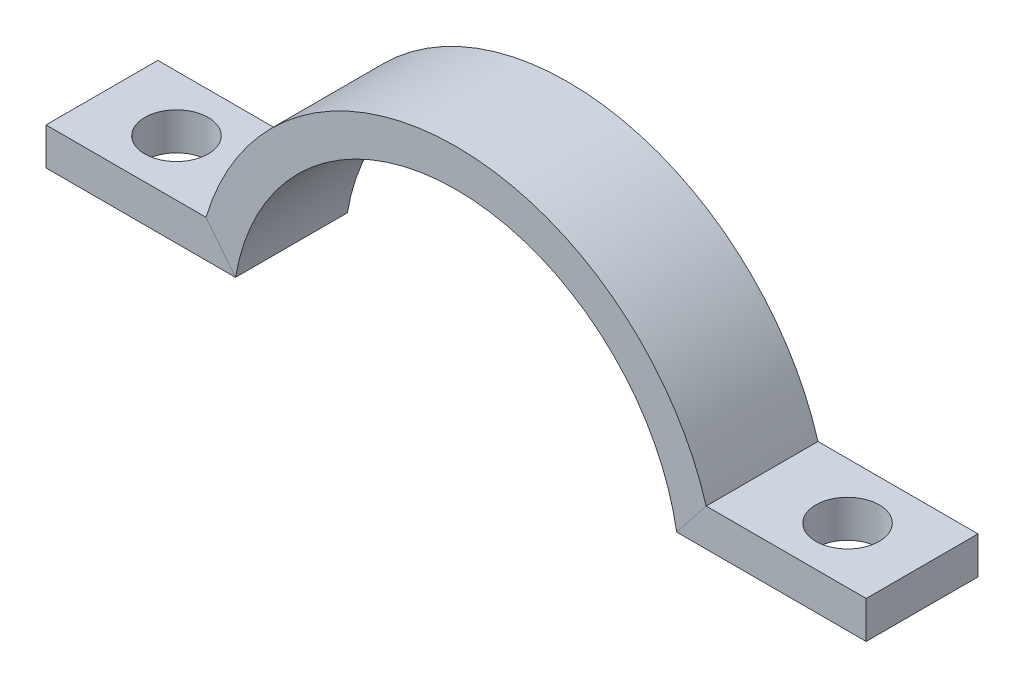
SolidWorks part; units mm, degrees
ref_plane "前基準面" through (0, 0, 0) normal (0, 0, 1) x (1, 0, 0)
ref_plane "上基準面" through (0, 0, 0) normal (0, 1, 0) x (1, 0, 0)
ref_plane "右基準面" through (0, 0, 0) normal (1, 0, 0) x (0, 0, -1)
sketch "草圖1" plane through (0, 0, 0) normal (0, 0, 1) x (1, 0, 0)
  line L0 (-22, 2) -> (-11.8322, 2)
  line L1 (-11.8322, 2) -> (11.8322, 2) construction
  line L2 (11.8322, 2) -> (22, 2)
  arc A0 (11.8322, 2) -> (-11.8322, 2) centre (0, 0) ccw
  arc A1 (-11.8322, 2) -> (11.8322, 2) centre (0, 0) ccw construction
  dimension "D1" = 24
  dimension "D2" = 2
  dimension "D3" = 22
ref_plane "平面1" through (22, 0, 0) normal (1, 0, 0) x (0, 0, -1)
sketch "草圖2" plane through (22, 0, 0) normal (1, 0, 0) x (0, 0, -1)
  line L0 (0, 12) -> (0, 2) construction
  line L1 (3, 2) -> (-3, 2)
  line L2 (3, 2) -> (3, 4)
  line L3 (3, 4) -> (-3, 4)
  line L4 (-3, 2) -> (-3, 4)
  line L5 (3, 2) -> (-3, 4) construction
  line L6 (3, 4) -> (-3, 2) construction
  point P0 (0, 3)
  point P10 (0, 2)
  dimension "D1" = 2
  dimension "D2" = 6
sweep "掃出1" add profiles "草圖2" path "草圖1"
hole_wizard "M3 餘隙孔1" positions "草圖3" profile "草圖5" hole size "M3" standard "ISO" end condition through all
sketch "草圖3" plane through (0, 4, 0) normal (0, 1, 0) x (1, 0, 0)
  line L0 (0, 0) -> (0, 10.0397) construction
  point P0 (-18, 0)
  point P2 (18, 0)
  dimension "D1" = 36
sketch "草圖5" plane through (-18, 4, 0) normal (1, 0, 0) x (0, 0, 1)
  line L0 (0, 0) -> (0, 2)
  line L1 (0, 2) -> (1.7, 2)
  line L2 (1.7, 2) -> (1.7, 0)
  line L5 (1.7, 0) -> (0, 0)
  line L11 (0, -6.35) -> (0, 107.95) construction
  dimension "貫穿孔直徑" = 3.4
  dimension "貫穿孔深度" = 2
